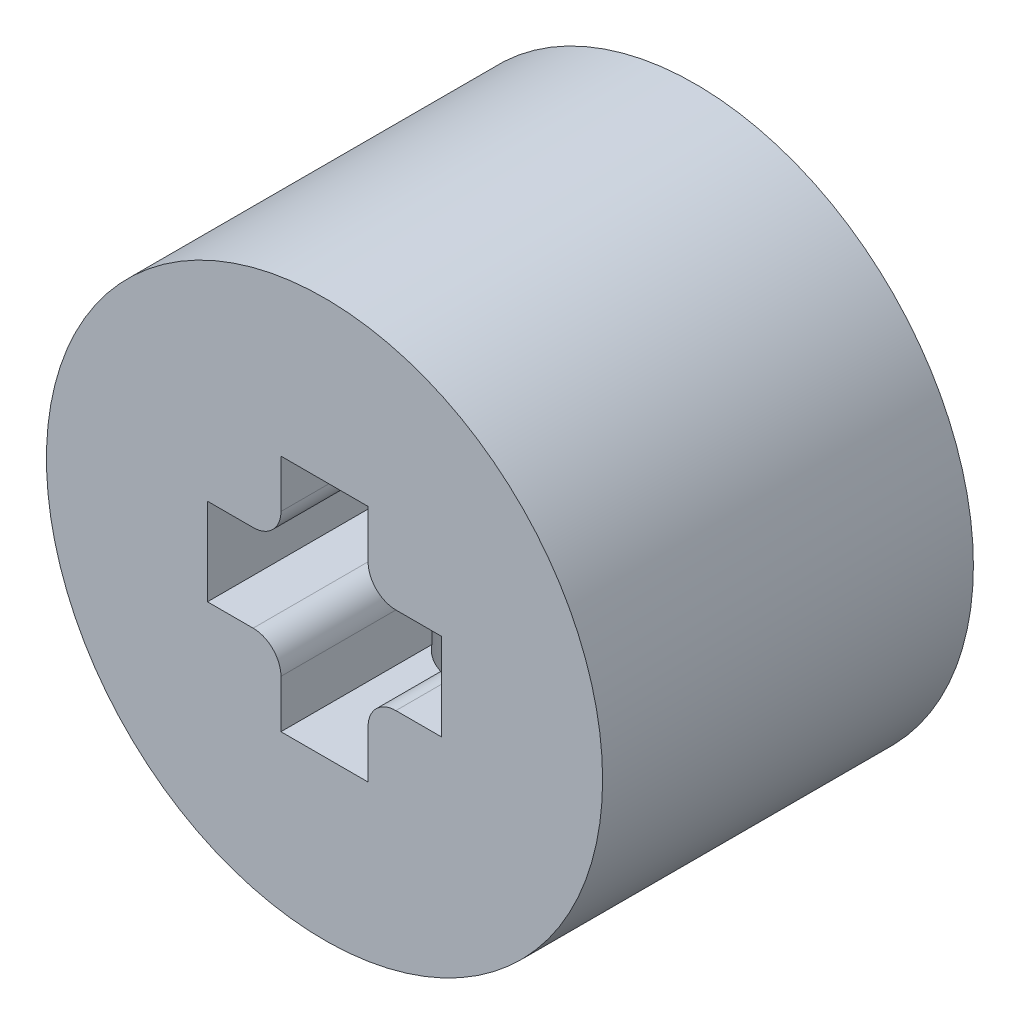
SolidWorks part; units mm, degrees
ref_plane "正面" through (0, 0, 0) normal (0, 0, 1) x (1, 0, 0)
ref_plane "平面" through (0, 0, 0) normal (0, 1, 0) x (1, 0, 0)
ref_plane "右側面" through (0, 0, 0) normal (1, 0, 0) x (0, 0, -1)
sketch "ｽｹｯﾁ1" plane through (0, 0, 0) normal (0, 0, 1) x (1, 0, 0)
  circle A0 centre (0, 0) radius 6
  dimension "D1" = 12
extrude "ﾎﾞｽ - 押し出し1" add sketch "ｽｹｯﾁ1" along normal blind 8
sketch "ｽｹｯﾁ2" plane through (0, 0, 8) normal (0, 0, 1) x (1, 0, 0)
  line L1 (-2.525, 0.94) -> (2.525, 0.94)
  line L2 (-2.525, 0.94) -> (-2.525, -0.94)
  line L3 (-2.525, -0.94) -> (2.525, -0.94)
  line L4 (2.525, 0.94) -> (2.525, -0.94)
  line L5 (-2.525, 0.94) -> (2.525, -0.94) construction
  line L6 (-2.525, -0.94) -> (2.525, 0.94) construction
  line L7 (-0.94, 2.575) -> (0.94, 2.575)
  line L8 (-0.94, 2.575) -> (-0.94, -2.575)
  line L9 (-0.94, -2.575) -> (0.94, -2.575)
  line L10 (0.94, 2.575) -> (0.94, -2.575)
  line L11 (-0.94, 2.575) -> (0.94, -2.575) construction
  line L12 (-0.94, -2.575) -> (0.94, 2.575) construction
  point P0 (0, 0)
  point P6 (0, 0)
  dimension "D1" = 5.15
  dimension "D2" = 5.05
  dimension "D3" = 1.88
  dimension "D4" = 1.88
extrude "ｶｯﾄ - 押し出し1" cut sketch "ｽｹｯﾁ2" against normal through all contours L1 L4 L3 L2 | L10 L9 L8 L7
fillet "ﾌｨﾚｯﾄ1" radius 0.6 4 edges at (-0.94, 0.94, 4) (-0.94, -0.94, 4) (0.94, -0.94, 4) (0.94, 0.94, 4)
sketch "ｽｹｯﾁ3" plane through (0, -2.575, 0) normal (0, 1, 0) x (1, 0, 0)
  line L0 (0, 0) -> (0, -8) construction
  line L1 (-6, -8) -> (6, -8) construction
  line L2 (0, -4) -> (5.4928, -4) construction
  circle A0 centre (0, -4) radius 1.2
  dimension "D1" = 2.4
extrude "ｶｯﾄ - 押し出し2" cut sketch "ｽｹｯﾁ3" against normal through all and the other way blind 0.5
